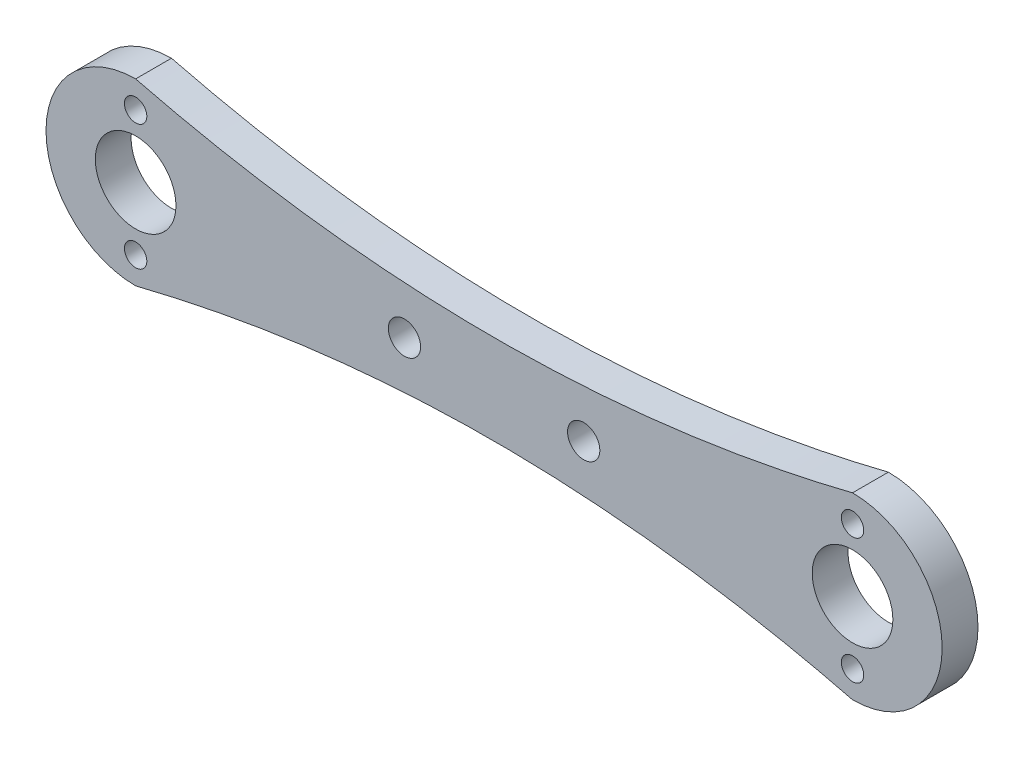
SolidWorks part; units mm, degrees
ref_plane "Plan de face" through (0, 0, 0) normal (0, 0, 1) x (1, 0, 0)
ref_plane "Plan de dessus" through (0, 0, 0) normal (0, 1, 0) x (1, 0, 0)
ref_plane "Plan de droite" through (0, 0, 0) normal (1, 0, 0) x (0, 0, -1)
sketch "Esquisse1" plane through (0, 0, 0) normal (0, 0, 1) x (1, 0, 0)
  line L0 (0, 0) -> (80, 0) construction
  line L1 (0, 10) -> (80, 10)
  line L2 (0, -10) -> (80, -10)
  line L3 (0, 7) -> (0, 0) construction
  line L4 (0, 0) -> (0, -7) construction
  line L5 (80, 7) -> (80, 0) construction
  line L6 (80, 0) -> (80, -7) construction
  line L7 (0, 10) -> (40, 0) construction
  line L8 (40, 0) -> (80, 10) construction
  line L9 (0, -10) -> (40, 0) construction
  line L10 (40, 0) -> (80, -10) construction
  line L11 (0, -4.5) -> (0, -10) construction
  line L12 (0, 10) -> (0, 7) construction
  line L13 (0, 7) -> (80, 7) construction
  line L14 (80, 7) -> (80, 10) construction
  line L15 (80, 10) -> (80, -10) construction
  arc A0 (0, 10) -> (0, -10) centre (0, 0) ccw
  arc A1 (80, -10) -> (80, 10) centre (80, 0) ccw
  circle A2 centre (0, 0) radius 4.5
  circle A3 centre (80, 0) radius 4.5
  circle A4 centre (0, 7) radius 1.25
  circle A5 centre (0, -7) radius 1.25
  circle A6 centre (80, 7) radius 1.25
  circle A7 centre (80, -7) radius 1.25
  spline S0 degree 2 poles (0, 10) (40, 0) (80, 10) knots 0 0 0 1 1 1
  spline S1 degree 2 poles (0, -10) (40, 0) (80, -10) knots 0 0 0 1 1 1
  point P27 (40, 0)
  dimension "D1" = 9
  dimension "D2" = 9
  dimension "D3" = 2.5
  dimension "D4" = 2.5
  dimension "D5" = 2.5
  dimension "D6" = 2.5
  dimension "D10" = 10
  dimension "D11" = 10
  dimension "D7" = 14
  dimension "D8" = 80
  dimension "D9" = 20
extrude "Boss.-Extru.1" add sketch "Esquisse1" along normal blind 4 contours A0 S1 A1 S0 A7 A6 A5 A4 A3 A2
sketch "Esquisse2" plane through (0, 0, 0) normal (0, 0, -1) x (-1, 0, 0)
  line L0 (-80, 0) -> (0, 0) construction
  line L1 (-80, 4.5) -> (-80, -4.5) construction
  circle A0 centre (-80, 0) radius 4.5 construction
  circle A1 centre (-50, 0) radius 1.8
  circle A2 centre (-30, 0) radius 1.8
  point P12 (-40, 0)
  dimension "D2" = 3.6
  dimension "D3" = 3.6
  dimension "D1" = 20
  dimension "D4" = 10
extrude "Enlèv. mat.-Extru.1" cut sketch "Esquisse2" against normal blind 10
